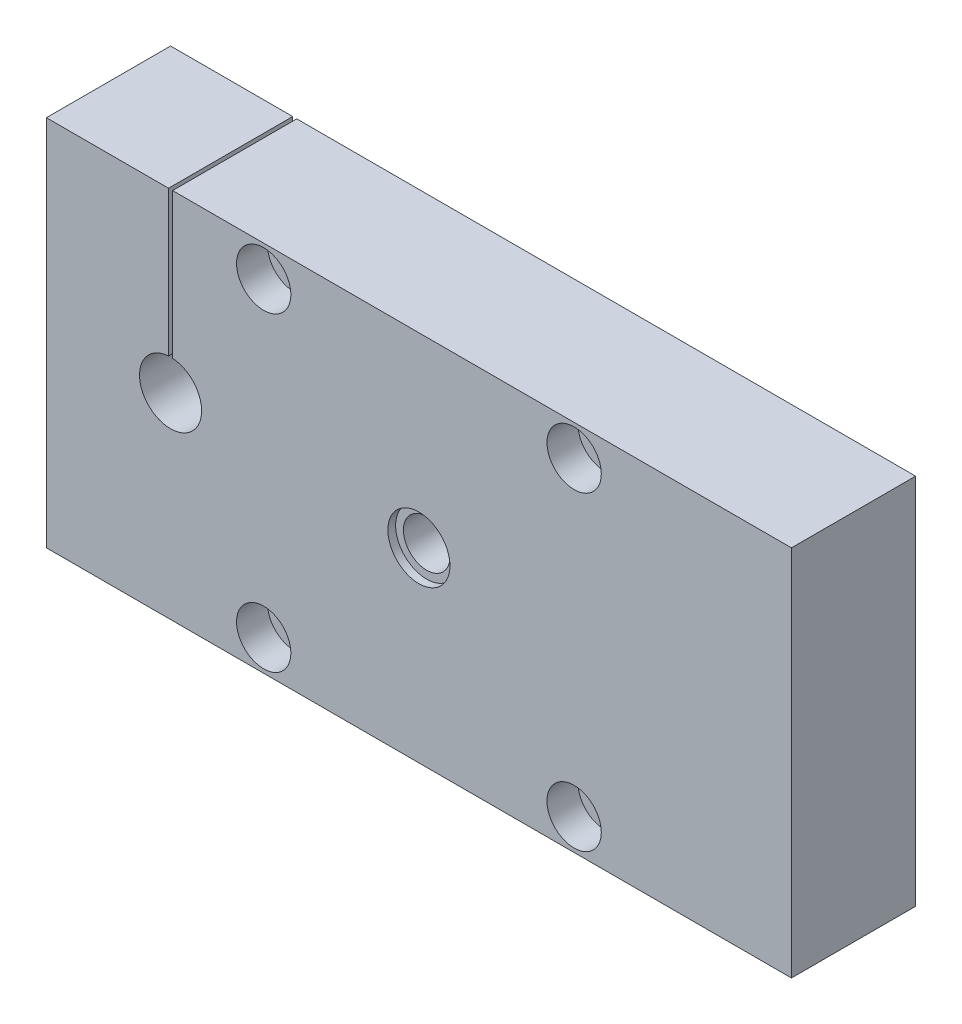
SolidWorks part; units mm, degrees
ref_plane "Front Plane" through (0, 0, 0) normal (0, 0, 1) x (1, 0, 0)
ref_plane "Top Plane" through (0, 0, 0) normal (0, 1, 0) x (1, 0, 0)
ref_plane "Right Plane" through (0, 0, 0) normal (1, 0, 0) x (0, 0, -1)
sketch "Sketch1" plane through (0, 0, 0) normal (0, 0, 1) x (1, 0, 0)
  line L1 (-75.7896, 70.263) -> (76.6104, 70.263)
  line L2 (-75.7896, 70.263) -> (-75.7896, -5.937)
  line L3 (-75.7896, -5.937) -> (76.6104, -5.937)
  line L4 (76.6104, 70.263) -> (76.6104, -5.937)
  dimension "D1" = 76.2
  dimension "D2" = 152.4
extrude "Boss-Extrude1" add sketch "Sketch1" along normal blind 25.4
hole_wizard "Hole1" positions "Sketch3" profile "Sketch2" legacy end condition through all
sketch "Sketch3" plane through (0, 0, 25.4) normal (0, 0, 1) x (1, 0, 0)
  line L0 (76.6104, 70.263) -> (-75.7896, 70.263) construction
  line L1 (-75.7896, 70.263) -> (-75.7896, -5.937) construction
  point P0 (0.4104, 32.163)
  point P4 (0.4104, 70.263)
  point P7 (-75.7896, 32.163)
sketch "Sketch2" plane through (0.4104, 32.163, 25.4) normal (1, 0, 0) x (0, -1, 0)
  line L0 (0, 0) -> (0, 25.4)
  line L1 (0, 25.4) -> (4.7625, 25.4)
  line L2 (4.7625, 25.4) -> (4.7625, 1.5875)
  line L3 (4.7625, 1.5875) -> (6.35, 1.5875)
  line L4 (6.35, 1.5875) -> (6.35, 0)
  line L5 (6.35, 0) -> (0, 0)
  line L6 (0, 110) -> (0, -10) construction
  dimension "Diameter" = 9.525
  dimension "Depth" = 25.4
  dimension "C-Bore Diameter" = 12.7
  dimension "C-Bore Depth" = 1.5875
hole_wizard "1/2 (0.5) Diameter Hole1" positions "Sketch5" profile "Sketch4" hole size "1/2" standard "ANSI Inch" end condition through all
sketch "Sketch5" plane through (0, 0, 25.4) normal (0, 0, 1) x (1, 0, 0)
  circle A0 centre (0.4104, 32.163) radius 4.7625 construction
  circle A1 centre (0.4104, 32.163) radius 6.35 construction
  point P0 (-50.3896, 34.2077)
  dimension "D2" = 50.8
  dimension "D3" = 2.0447
sketch "Sketch4" plane through (-50.3896, 34.2077, 25.4) normal (1, 0, 0) x (0, -1, 0)
  line L0 (0, 0) -> (0, 25.4)
  line L1 (0, 25.4) -> (6.35, 25.4)
  line L2 (6.35, 25.4) -> (6.35, 0)
  line L5 (6.35, 0) -> (0, 0)
  line L11 (0, -6.35) -> (0, 107.95) construction
  dimension "Thru Hole Dia." = 12.7
  dimension "Thru Hole Depth" = 25.4
hole_wizard "CBORE for 1/4 Socket Head Cap Screw1" positions "Sketch12" profile "Sketch11" counterbore size "1/4" standard "Ansi Inch" end condition through all
sketch "Sketch12" plane through (0, 0, 25.4) normal (0, 0, 1) x (1, 0, 0)
  line L0 (0.4104, 32.163) -> (0.4104, -23.7304) construction
  line L2 (0.4104, 32.163) -> (-39.039, 32.163) construction
  point P0 (-31.3396, 63.913)
  point P22 (-31.3396, 0.413)
  point P23 (32.1604, 0.413)
  point P24 (32.1604, 63.913)
  dimension "D1" = 63.5
  dimension "D2" = 63.5
sketch "Sketch11" plane through (-31.3396, 63.913, 25.4) normal (1, 0, 0) x (0, -1, 0)
  line L0 (0, 0) -> (0, 25.4)
  line L1 (0, 25.4) -> (3.3782, 25.4)
  line L3 (3.3782, 25.4) -> (3.3782, 6.35)
  line L4 (3.3782, 6.35) -> (5.5562, 6.35)
  line L5 (5.5562, 6.35) -> (5.5562, 0)
  line L7 (5.5562, 0) -> (0, 0)
  line L11 (0, -6.35) -> (0, 107.95) construction
  dimension "Thru Hole Dia." = 6.7564
  dimension "Thru Hole Depth" = 25.4
  dimension "C'Bore Dia." = 11.1125
  dimension "C'Bore Depth" = 6.35
sketch "Sketch14" plane through (0, 0, 0) normal (0, 0, -1) x (-1, 0, 0)
  line L0 (75.7896, -5.937) -> (-76.6104, -5.937) construction
  line L2 (-13.1104, 32.163) -> (-13.1104, -5.937)
  line L3 (-13.1104, -5.937) -> (12.2896, -5.937)
  line L4 (12.2896, 32.163) -> (12.2896, -5.937)
  arc A0 (12.2896, 32.163) -> (-13.1104, 32.163) centre (-0.4104, 32.163) ccw
  dimension "D1" = 12.7
extrude "Cut-Extrude2" cut sketch "Sketch14" against normal blind 12.7
sketch "Sketch17" plane through (0, 0, 25.4) normal (0, 0, 1) x (1, 0, 0)
  line L0 (-75.7896, 70.263) -> (-75.7896, -5.937) construction
  line L1 (-75.7896, 19.463) -> (-59.9146, 19.463)
  line L2 (-75.7896, 19.463) -> (-75.7896, 70.263)
  line L3 (-75.7896, 70.263) -> (-59.9146, 70.263)
  line L4 (-59.9146, 19.463) -> (-59.9146, 70.263)
  line L5 (76.6104, 70.263) -> (-75.7896, 70.263) construction
  line L6 (76.6104, -5.937) -> (76.6104, 70.263) construction
  line L7 (76.6104, 19.463) -> (60.7354, 19.463)
  line L8 (76.6104, 19.463) -> (76.6104, 70.263)
  line L9 (76.6104, 70.263) -> (60.7354, 70.263)
  line L10 (60.7354, 19.463) -> (60.7354, 70.263)
  dimension "D1" = 50.8
  dimension "D2" = 15.875
sketch "Sketch22" plane through (0, 0, 25.4) normal (0, 0, 1) x (1, 0, 0)
  line L0 (76.6104, 70.263) -> (-75.7896, 70.263) construction
  line L1 (-50.8023, 40.5443) -> (-49.9768, 40.5443)
  line L2 (-50.8023, 40.5443) -> (-50.8023, 70.263)
  line L3 (-50.8023, 70.263) -> (-49.9768, 70.263)
  line L4 (-49.9768, 40.5443) -> (-49.9768, 70.263)
  circle A0 centre (-50.3896, 34.2077) radius 6.35 construction
  dimension "D1" = 0.8255
extrude "Cut-Extrude4" cut sketch "Sketch22" against normal through all
